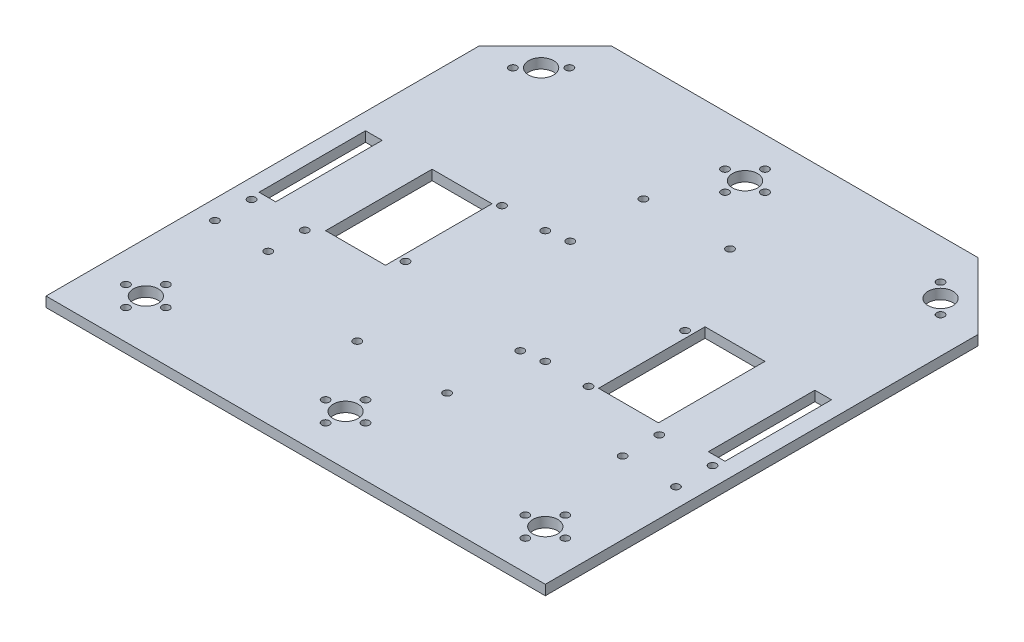
SolidWorks part; units mm, degrees
ref_plane "Plan de face" through (0, 0, 0) normal (0, 0, 1) x (1, 0, 0)
ref_plane "Plan de dessus" through (0, 0, 0) normal (0, 1, 0) x (1, 0, 0)
ref_plane "Plan de droite" through (0, 0, 0) normal (1, 0, 0) x (0, 0, -1)
sketch "Esquisse1" plane through (0, 0, 0) normal (0, 1, 0) x (1, 0, 0)
  line L0 (-150, 0) -> (-150, 260)
  line L2 (150, 0) -> (150, 260)
  line L3 (-150, 260) -> (-110, 260) construction
  line L4 (-110, 260) -> (-110, 300) construction
  line L5 (150, 260) -> (110, 260) construction
  line L6 (110, 260) -> (110, 300) construction
  line L8 (-150, 260) -> (-110, 300)
  line L9 (-110, 300) -> (110, 300)
  line L11 (110, 300) -> (150, 260)
  line L12 (-150, 0) -> (-120, 0) construction
  line L13 (-120, 18) -> (-120, 0) construction
  line L14 (150, 0) -> (120, 0) construction
  line L15 (120, 18) -> (120, 0) construction
  line L17 (-150, 260) -> (-120, 260) construction
  line L18 (-120, 260) -> (-120, 267.5) construction
  line L19 (150, 260) -> (120, 260) construction
  line L20 (120, 260) -> (120, 267.5) construction
  line L21 (-120, 267.5) -> (-111.5147, 275.9853) construction
  line L22 (-120, 267.5) -> (-128.4853, 259.0147) construction
  line L23 (120, 267.5) -> (128.4853, 259.0147) construction
  line L24 (120, 267.5) -> (111.5147, 275.9853) construction
  line L25 (-150, 0) -> (150, 0) construction
  line L26 (120, 30) -> (120, 18) construction
  line L27 (120, 30) -> (120, 42) construction
  line L28 (-150, 0) -> (150, 0)
  line L29 (-120, 18) -> (-120, 30) construction
  line L30 (-120, 30) -> (-120, 42) construction
  line L31 (0, 0) -> (0, 30) construction
  line L32 (150, 150) -> (-150, 150) construction
  line L33 (-120, 30) -> (-108, 30) construction
  line L34 (-120, 30) -> (-132, 30) construction
  line L35 (120, 30) -> (132, 30) construction
  line L36 (120, 30) -> (108, 30) construction
  line L37 (0, 30) -> (12, 30) construction
  line L38 (12, 30) -> (0, 30) construction
  line L39 (0, 30) -> (-12, 30) construction
  line L40 (0, 30) -> (0, 42) construction
  line L41 (0, 42) -> (0, 18) construction
  line L42 (0, 300) -> (0, 270) construction
  line L43 (0, 270) -> (12, 270) construction
  line L44 (0, 270) -> (-12, 270) construction
  line L45 (-12, 270) -> (0, 270) construction
  line L46 (0, 270) -> (0, 258) construction
  line L47 (0, 258) -> (0, 282) construction
  line L48 (0, 300) -> (0, 0) construction
  circle A2 centre (-120, 30) radius 7.5
  circle A4 centre (-120, 267.5) radius 7.5
  circle A5 centre (120, 267.5) radius 7.5
  circle A6 centre (-111.5147, 275.9853) radius 2.3
  circle A7 centre (-128.4853, 259.0147) radius 2.3
  circle A8 centre (111.5147, 275.9853) radius 2.3
  circle A9 centre (128.4853, 259.0147) radius 2.3
  circle A10 centre (120, 30) radius 7.5
  circle A11 centre (120, 42) radius 2.3
  circle A13 centre (-120, 42) radius 2.3
  circle A14 centre (-120, 18) radius 2.3
  circle A16 centre (-132, 30) radius 2.3
  circle A17 centre (-108, 30) radius 2.3
  circle A18 centre (108, 30) radius 2.3
  circle A19 centre (132, 30) radius 2.3
  circle A20 centre (120, 18) radius 2.3
  circle A21 centre (0, 30) radius 7.5
  circle A22 centre (0, 18) radius 2.3
  circle A23 centre (12, 30) radius 2.3
  circle A24 centre (0, 42) radius 2.3
  circle A25 centre (-12, 30) radius 2.3
  circle A26 centre (0, 270) radius 7.5
  circle A27 centre (-12, 270) radius 2.3
  circle A28 centre (0, 282) radius 2.3
  circle A29 centre (12, 270) radius 2.34
  circle A30 centre (0, 258) radius 2.3
extrude "Boss.-Extru.1" add sketch "Esquisse1" along normal blind 6
sketch "Esquisse7" plane through (0, 6, 0) normal (0, 1, 0) x (1, 0, 0)
  line L0 (-130, 150) -> (0, 150) construction
  line L2 (150, 150) -> (-150, 150) construction
  line L3 (-130, 150) -> (-130, 182)
  line L4 (-130, 182) -> (-140, 182)
  line L5 (-140, 182) -> (-140, 118)
  line L6 (-140, 118) -> (-130, 118)
  line L7 (-130, 118) -> (-130, 150)
extrude "Enlèv. mat.-Extru.9" cut sketch "Esquisse7" against normal blind 10.5
sketch "Esquisse6" plane through (0, 6, 0) normal (0, 1, 0) x (1, 0, 0)
  line L0 (-142.5, 116) -> (-134.5, 116) construction
  line L2 (-142.5, 116) -> (-142.5, 150) construction
  line L3 (-142.5, 116) -> (-142.5, 108) construction
  line L11 (-142.5, 108) -> (-134.5, 108) construction
  line L12 (-134.5, 108) -> (-134.5, 116) construction
  line L14 (-142.5, 150) -> (-150, 150) construction
  line L15 (-142.5, 116) -> (-102.5, 116) construction
  line L16 (-102.5, 116) -> (-102.5, 108) construction
  line L17 (-102.5, 108) -> (-110.5, 108) construction
  line L18 (-110.5, 108) -> (-110.5, 116) construction
  line L19 (-110.5, 116) -> (-134.5, 116) construction
  line L20 (-134.5, 116) -> (-134.5, 86) construction
  line L21 (-134.5, 86) -> (-142.5, 86) construction
  line L22 (-142.5, 86) -> (-142.5, 94) construction
  line L23 (-142.5, 94) -> (-134.5, 94) construction
  line L24 (-134.5, 94) -> (-134.5, 86) construction
  line L25 (-134.5, 86) -> (-110.5, 86) construction
  line L26 (-110.5, 86) -> (-110.5, 94) construction
  line L27 (-110.5, 94) -> (-102.5, 94) construction
  line L28 (-102.5, 94) -> (-102.5, 86) construction
  line L29 (-102.5, 86) -> (-110.5, 86) construction
  line L30 (-102.5, 94) -> (-110.5, 86) construction
  line L31 (-110.5, 94) -> (-102.5, 86) construction
  line L32 (-142.5, 94) -> (-134.5, 86) construction
  line L33 (-142.5, 86) -> (-134.5, 94) construction
  line L34 (-142.5, 116) -> (-134.5, 108) construction
  line L35 (-142.5, 108) -> (-134.5, 116) construction
  line L71 (-110.5, 116) -> (-102.5, 108) construction
  line L72 (-110.5, 108) -> (-102.5, 116) construction
  line L73 (-110.5, 116) -> (-110.5, 86) construction
  circle A20 centre (-138.5, 90) radius 2.3
  circle A21 centre (-138.5, 112) radius 2.3
  circle A22 centre (-106.5, 112) radius 2.3
  circle A23 centre (-106.5, 90) radius 2.3
  dimension "D1" = 7.5
  dimension "D2" = 34
sketch "Esquisse4" plane through (0, 6, 0) normal (0, 1, 0) x (1, 0, 0)
  line L0 (-150, 150) -> (-100, 150) construction
  line L1 (-100, 118) -> (-100, 182)
  line L2 (-100, 182) -> (-64, 182)
  line L8 (150, 150) -> (-150, 150) construction
  line L17 (-100, 118) -> (-64, 118)
  line L18 (-64, 118) -> (-64, 182)
extrude "Enlèv. mat.-Extru.10" cut sketch "Esquisse6" against normal blind 50
extrude "Enlèv. mat.-Extru.11" cut sketch "Esquisse4" against normal blind 50
mirror "Symétrie1" about plane through (0, 0, 0) normal (1, 0, 0) of "Enlèv. mat.-Extru.9"
mirror "Symétrie2" about plane through (0, 0, 0) normal (1, 0, 0) of "Enlèv. mat.-Extru.11"
mirror "Symétrie3" about plane through (0, 0, 0) normal (1, 0, 0) of "Enlèv. mat.-Extru.10"
sketch "Esquisse11" plane through (0, 6, 0) normal (0, 1, 0) x (1, 0, 0)
  line L0 (-64, 150) -> (-64, 130) construction
  line L1 (-30, 74) -> (-37, 74) construction
  line L2 (-64, 118) -> (-64, 182) construction
  line L3 (30, 226) -> (-25, 226) construction
  line L4 (-25, 226) -> (-25, 190) construction
  line L5 (-25, 190) -> (-17, 190) construction
  line L6 (-17, 190) -> (-17, 182) construction
  line L7 (-64, 150) -> (-64, 180) construction
  line L8 (-64, 180) -> (-30, 180) construction
  line L9 (-30, 180) -> (-30, 74) construction
  line L10 (-64, 130) -> (-56, 130) construction
  line L11 (-56, 130) -> (-56, 122) construction
  line L12 (-56, 122) -> (-64, 130) construction
  line L13 (-64, 130) -> (-56, 130) construction
  line L14 (-56, 130) -> (-64, 122) construction
  line L15 (-64, 122) -> (-56, 122) construction
  line L16 (-64, 180) -> (-64, 188) construction
  line L17 (-64, 188) -> (-56, 188) construction
  line L18 (-56, 188) -> (-56, 180) construction
  line L19 (-56, 180) -> (-64, 188) construction
  line L20 (-64, 188) -> (-56, 188) construction
  line L21 (64, 150) -> (64, 170) construction
  line L22 (64, 170) -> (56, 170) construction
  line L23 (56, 170) -> (56, 178) construction
  line L24 (56, 178) -> (64, 178) construction
  line L25 (64, 178) -> (64, 170) construction
  line L26 (64, 170) -> (56, 178) construction
  line L27 (56, 178) -> (56, 170) construction
  line L28 (56, 170) -> (64, 178) construction
  line L29 (64, 150) -> (64, 120) construction
  line L30 (64, 118) -> (64, 182) construction
  line L31 (64, 120) -> (30, 120) construction
  line L32 (30, 120) -> (30, 165) construction
  line L33 (30, 165) -> (37, 165) construction
  line L34 (37, 165) -> (37, 129.3158) construction
  line L35 (37, 129.3158) -> (64, 129.3158) construction
  line L36 (30, 120) -> (30, 226) construction
  line L37 (-17, 182) -> (-25, 182) construction
  line L38 (-25, 182) -> (-25, 190) construction
  line L39 (-25, 190) -> (-17, 182) construction
  line L40 (-17, 182) -> (-17, 190) construction
  line L41 (-17, 190) -> (-25, 182) construction
  line L42 (30, 226) -> (35, 226) construction
  line L43 (35, 226) -> (35, 234) construction
  line L44 (35, 234) -> (27, 234) construction
  line L45 (-25, 226) -> (-25, 234) construction
  line L46 (-25, 234) -> (-17, 234) construction
  line L47 (64, 120) -> (64, 112) construction
  line L48 (64, 112) -> (56, 112) construction
  line L49 (56, 112) -> (56, 120) construction
  line L50 (56, 120) -> (64, 112) construction
  line L51 (64, 112) -> (64, 120) construction
  line L52 (64, 120) -> (56, 112) construction
  line L53 (56, 112) -> (56, 120) construction
  line L54 (56, 120) -> (30, 120) construction
  line L55 (30, 120) -> (30, 112) construction
  line L56 (30, 112) -> (38, 112) construction
  line L57 (38, 112) -> (38, 120) construction
  line L58 (38, 120) -> (30, 112) construction
  line L59 (30, 112) -> (30, 120) construction
  line L60 (30, 120) -> (38, 112) construction
  line L61 (-17, 234) -> (-17, 226) construction
  line L62 (-17, 226) -> (-25, 234) construction
  line L63 (-25, 234) -> (-25, 226) construction
  line L64 (-25, 226) -> (-17, 234) construction
  line L65 (27, 234) -> (27, 226) construction
  line L66 (27, 226) -> (35, 234) construction
  line L67 (35, 234) -> (27, 234) construction
  line L68 (27, 234) -> (35, 226) construction
  line L69 (-56, 188) -> (-64, 180) construction
  line L70 (-64, 180) -> (-30, 180) construction
  line L71 (-30, 180) -> (-30, 188) construction
  line L72 (-30, 188) -> (-38, 188) construction
  line L73 (-38, 188) -> (-38, 180) construction
  line L74 (-38, 180) -> (-30, 188) construction
  line L75 (-30, 188) -> (-38, 188) construction
  line L76 (-38, 188) -> (-30, 180) construction
  line L77 (-30, 180) -> (-30, 74) construction
  line L78 (-37, 74) -> (-37, 66) construction
  line L79 (-37, 66) -> (-29, 66) construction
  line L80 (-29, 66) -> (-37, 74) construction
  line L81 (-37, 74) -> (-37, 66) construction
  line L82 (-37, 66) -> (-29, 74) construction
  line L83 (-30, 74) -> (25, 74) construction
  line L84 (25, 74) -> (25, 110) construction
  line L85 (25, 110) -> (25, 118) construction
  line L86 (25, 118) -> (17, 118) construction
  line L87 (17, 118) -> (25, 110) construction
  line L88 (25, 110) -> (25, 118) construction
  line L89 (25, 118) -> (17, 110) construction
  line L90 (25, 74) -> (25, 66) construction
  line L91 (25, 66) -> (17, 66) construction
  line L92 (17, 66) -> (25, 74) construction
  line L93 (25, 74) -> (25, 66) construction
  line L94 (25, 66) -> (17, 74) construction
  circle A4 centre (34, 116) radius 2.3
  circle A5 centre (60, 116) radius 2.3
  circle A7 centre (60, 174) radius 2.3
  circle A8 centre (-21, 230) radius 2.3
  circle A12 centre (-21, 186) radius 2.3
  circle A13 centre (31, 230) radius 2.3
  circle A18 centre (-60, 126) radius 2.3
  circle A19 centre (-34, 184) radius 2.3
  circle A20 centre (-60, 184) radius 2.3
  circle A21 centre (-33, 70) radius 2.34
  circle A22 centre (21, 70) radius 2.3
  circle A23 centre (21, 114) radius 2.3
  dimension "D1" = 50
  dimension "D2" = 34
  dimension "D3" = 20
extrude "Enlèv. mat.-Extru.15" cut sketch "Esquisse11" against normal blind 10
